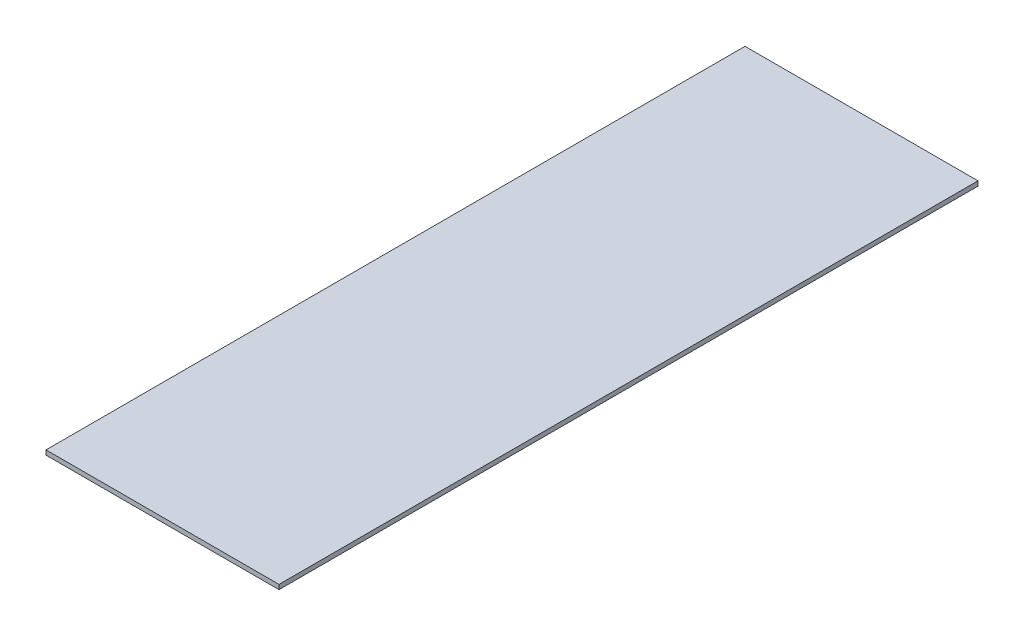
SolidWorks part; units mm, degrees
ref_plane "Front Plane" through (0, 0, 0) normal (0, 0, 1) x (1, 0, 0)
ref_plane "Top Plane" through (0, 0, 0) normal (0, 1, 0) x (1, 0, 0)
ref_plane "Right Plane" through (0, 0, 0) normal (1, 0, 0) x (0, 0, -1)
sketch "Sketch1" plane through (0, 0, 0) normal (0, 1, 0) x (1, 0, 0)
  line L1 (-14.3662, 131.9615) -> (36.4338, 131.9615)
  line L2 (-14.3662, 131.9615) -> (-14.3662, -20.4385)
  line L3 (-14.3662, -20.4385) -> (36.4338, -20.4385)
  line L4 (36.4338, 131.9615) -> (36.4338, -20.4385)
  dimension "D1" = 50.8
  dimension "D2" = 152.4
extrude "Boss-Extrude1" add sketch "Sketch1" along normal blind 1
